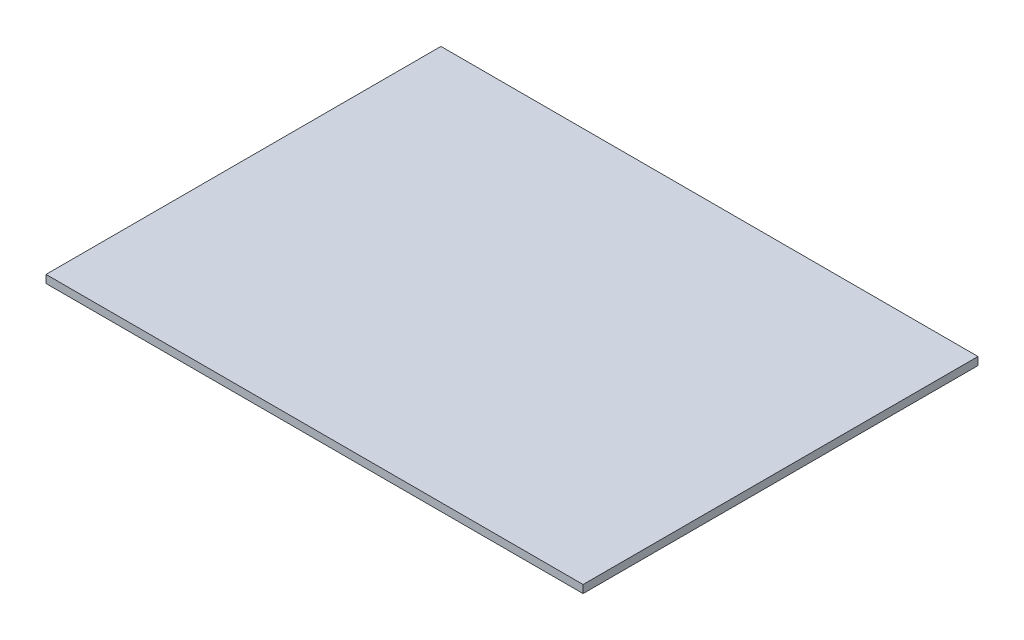
SolidWorks part; units mm, degrees
ref_plane "Front Plane" through (0, 0, 0) normal (0, 0, 1) x (1, 0, 0)
ref_plane "Top Plane" through (0, 0, 0) normal (0, 1, 0) x (1, 0, 0)
ref_plane "Right Plane" through (0, 0, 0) normal (1, 0, 0) x (0, 0, -1)
sketch "Sketch1" plane through (0, 0, 0) normal (0, 1, 0) x (1, 0, 0)
  line L1 (-170, -125) -> (170, -125)
  line L2 (-170, -125) -> (-170, 125)
  line L3 (-170, 125) -> (170, 125)
  line L4 (170, -125) -> (170, 125)
  line L5 (-170, -125) -> (170, 125) construction
  line L6 (-170, 125) -> (170, -125) construction
  point P0 (0, 0)
  dimension "D1" = 340
  dimension "D2" = 250
extrude "Boss-Extrude1" add sketch "Sketch1" along normal blind 5
